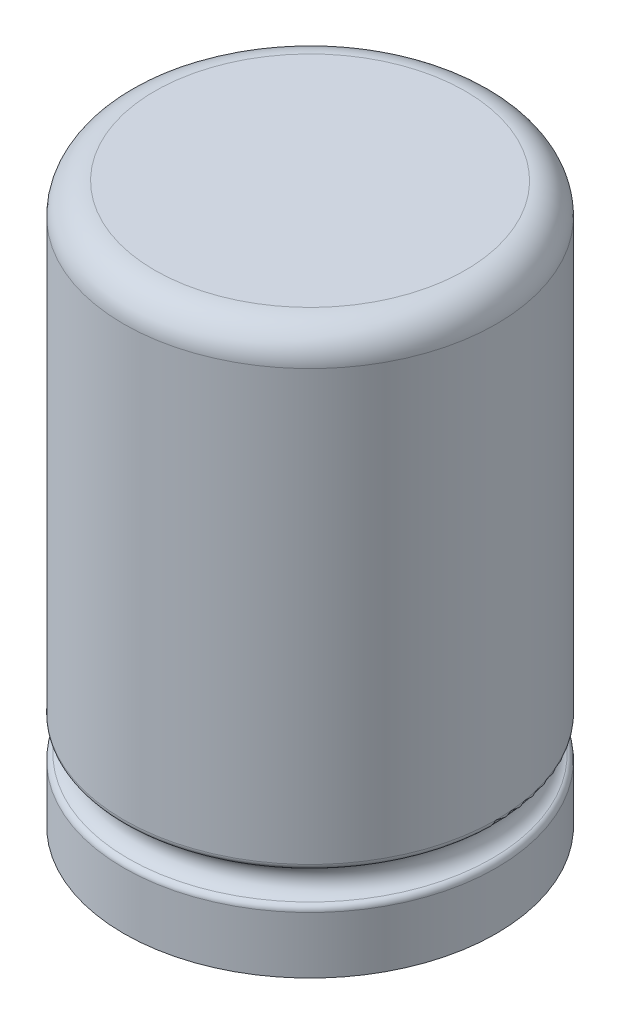
SolidWorks part; units mm, degrees
ref_plane "Front Plane" through (0, 0, 0) normal (0, 0, 1) x (1, 0, 0)
ref_plane "Top Plane" through (0, 0, 0) normal (0, 1, 0) x (1, 0, 0)
ref_plane "Right Plane" through (0, 0, 0) normal (1, 0, 0) x (0, 0, -1)
sketch "Sketch1" plane through (0, 0, 0) normal (0, 0, 1) x (1, 0, 0)
  line L0 (0, -5.1304) -> (0, 7.8969) construction
  line L1 (0, 0) -> (3, 0)
  line L3 (3, 1.5) -> (3, 8.5)
  line L4 (2.5, 9) -> (0, 9)
  line L5 (0, 0) -> (0, 9)
  line L6 (3, 1) -> (3, 0)
  arc A1 (3, 8.5) -> (2.5, 9) centre (2.5, 8.5) ccw
  arc A2 (3, 1.5) -> (3, 1) centre (3, 1.25) ccw
  point P5 (3, 1.25)
  point P13 (3, 9)
  dimension "D5" = 0.5
  dimension "D1" = 3
  dimension "D4" = 9
revolve "Revolve1" add sketch "Sketch1" angle 360 about L0
fillet "Fillet1" radius 0.1 2 edges at (0, 1.5, -3) (0, 1, -3)
